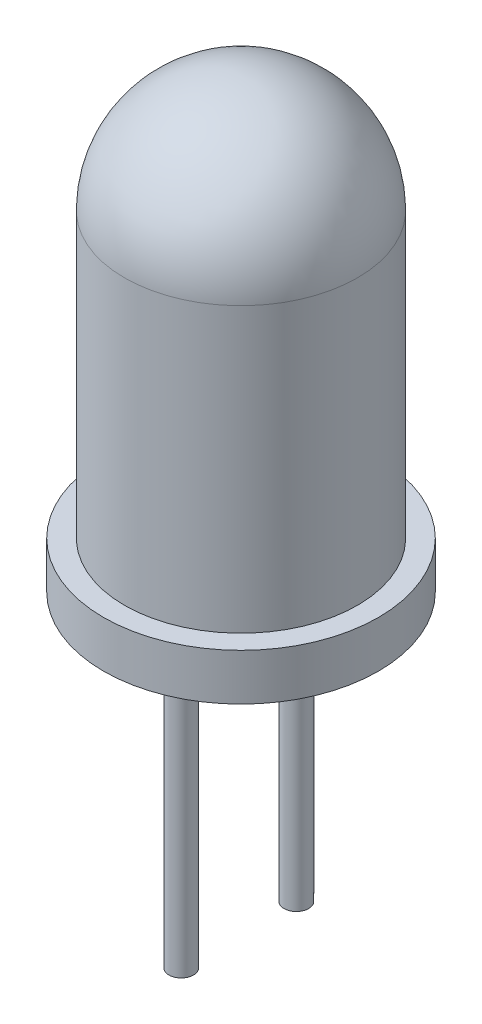
SolidWorks part; units mm, degrees
ref_plane "Front Plane" through (0, 0, 0) normal (0, 0, 1) x (1, 0, 0)
ref_plane "Top Plane" through (0, 0, 0) normal (0, 1, 0) x (1, 0, 0)
ref_plane "Right Plane" through (0, 0, 0) normal (1, 0, 0) x (0, 0, -1)
sketch "Sketch1" plane through (0, 0, 0) normal (1, 0, 0) x (0, 0, -1)
  line L0 (-2.5, 0) -> (-2.5, -6.09)
  line L1 (2.5, -6.09) -> (2.95, -6.09)
  line L2 (2.5, -6.09) -> (2.5, 0)
  line L3 (0, 2.5) -> (6.25, 2.5) construction
  line L4 (-2.95, -6.09) -> (-2.5, -6.09)
  line L5 (-2.95, -6.09) -> (-2.95, -7.09)
  line L6 (-2.95, -7.09) -> (2.95, -7.09)
  line L7 (2.95, -6.09) -> (2.95, -7.09)
  line L8 (0, 2.5) -> (0, -7.09)
  arc A0 (2.5, 0) -> (-2.5, 0) centre (0, 0) ccw
  point P12 (0, 2.5)
  point P13 (0, 2.5)
  point P15 (0, -7.09)
  dimension "D1" = 5
  dimension "D2" = 1
  dimension "D3" = 8.59
  dimension "D4" = 5.9
revolve "Revolve6" add sketch "Sketch1" angle 360 about L8
sketch "Sketch2" plane through (0, -7.09, 0) normal (0, -1, 0) x (1, 0, 0)
  line L0 (0, -1.1883) -> (0, 0.0475) construction
  line L1 (0, 0.0475) -> (0, 1.2833) construction
  circle A0 centre (0, 1.2833) radius 0.2648
  circle A1 centre (0, -1.1883) radius 0.2648
extrude "Boss-Extrude1" add sketch "Sketch2" along normal blind 6.35
